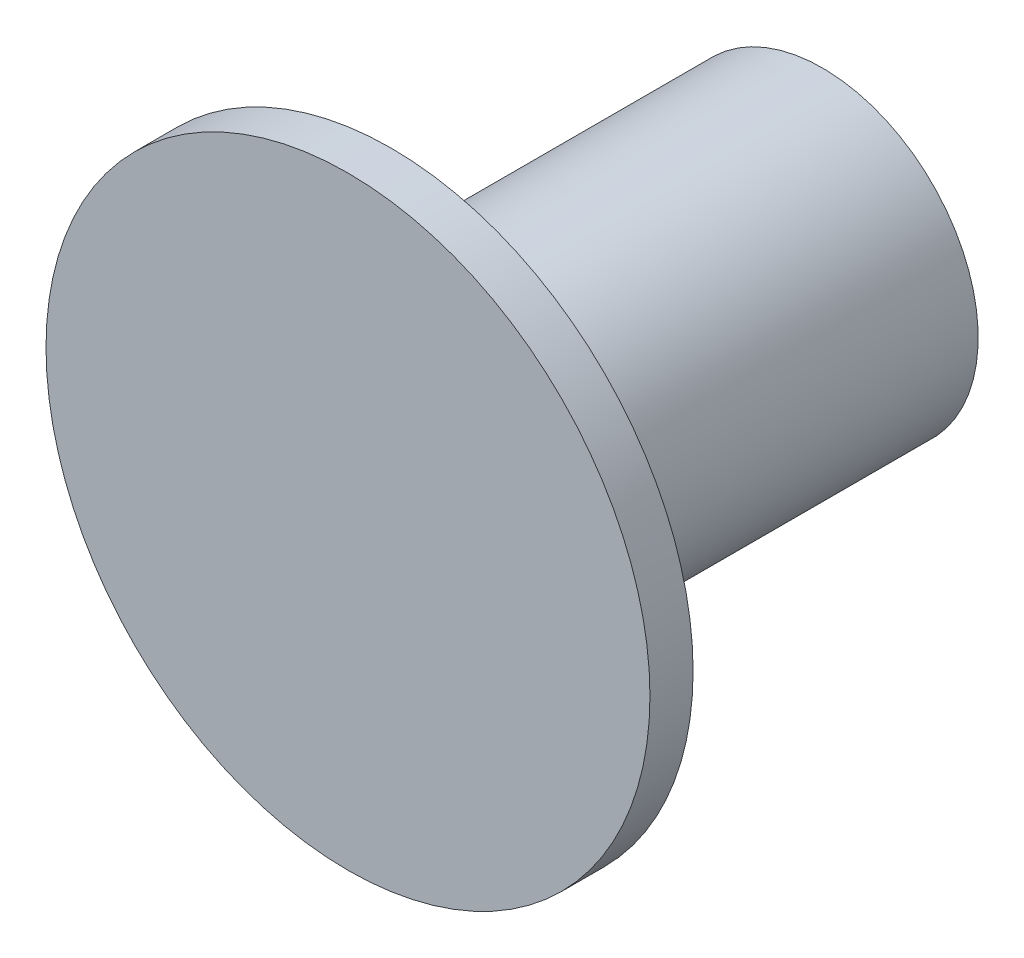
SolidWorks part; units mm, degrees
ref_plane "Front Plane" through (0, 0, 0) normal (0, 0, 1) x (1, 0, 0)
ref_plane "Top Plane" through (0, 0, 0) normal (0, 1, 0) x (1, 0, 0)
ref_plane "Right Plane" through (0, 0, 0) normal (1, 0, 0) x (0, 0, -1)
sketch "Sketch1" plane through (0, 0, 0) normal (0, 0, 1) x (1, 0, 0)
  circle A0 centre (0, 0) radius 1.778
extrude "Boss-Extrude1" add sketch "Sketch1" along normal blind 6.35
sketch "Sketch5" plane through (0, 0, 0) normal (0, 0, -1) x (-1, 0, 0)
  line L0 (0, 0) -> (0.9166, 0)
  circle A0 centre (0, 0) radius 0.9166
  circle A1 centre (0, 0) radius 1.778
  circle M2 centre (0, 0) radius 1.778
  dimension "D1" = 0.9166
extrude "Cut-Extrude3" cut sketch "Sketch5" against normal blind 6.096 contours A0 M2
sketch "Sketch6" plane through (0, 0, 0) normal (0, 0, -1) x (-1, 0, 0)
  circle A0 centre (0, 0) radius 0.9166
extrude "Cut-Extrude4" cut sketch "Sketch6" against normal blind 3.556
